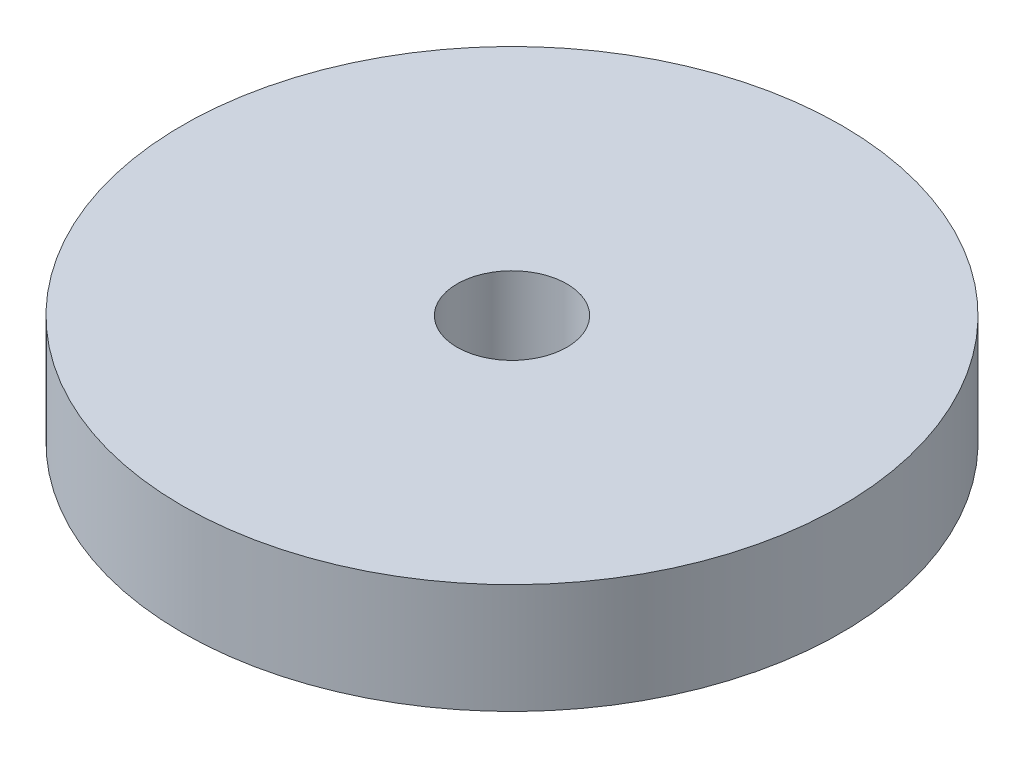
SolidWorks part; units mm, degrees
ref_plane "Front Plane" through (0, 0, 0) normal (0, 0, 1) x (1, 0, 0)
ref_plane "Top Plane" through (0, 0, 0) normal (0, 1, 0) x (1, 0, 0)
ref_plane "Right Plane" through (0, 0, 0) normal (1, 0, 0) x (0, 0, -1)
sketch "Sketch1" plane through (0, 0, 0) normal (0, 1, 0) x (1, 0, 0)
  circle A0 centre (0, 0) radius 15
  circle A1 centre (0, 0) radius 2.5
  dimension "D1" = 5
  dimension "D2" = 30
extrude "Boss-Extrude1" add sketch "Sketch1" along normal blind 5
